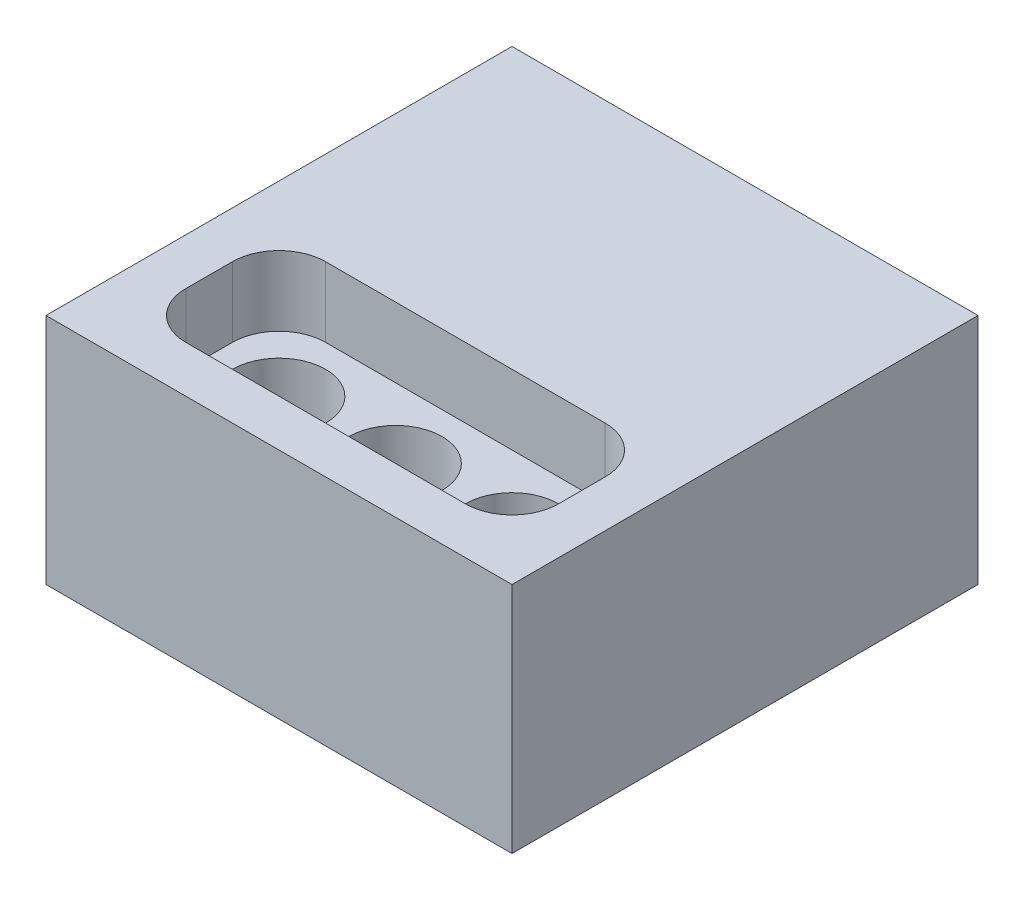
SolidWorks part; units mm, degrees
material "Steel, Hot Worked, AISI 1095"
ref_plane "Front Plane" through (0, 0, 0) normal (0, 0, 1) x (1, 0, 0)
ref_plane "Top Plane" through (0, 0, 0) normal (0, 1, 0) x (1, 0, 0)
ref_plane "Right Plane" through (0, 0, 0) normal (1, 0, 0) x (0, 0, -1)
sketch "Sketch1" plane through (0, 0, 0) normal (0, 1, 0) x (1, 0, 0)
  line L1 (0, 0) -> (100, 0)
  line L2 (0, 0) -> (0, 100)
  line L3 (0, 100) -> (100, 100)
  line L4 (100, 0) -> (100, 100)
  dimension "D1" = 100
  dimension "D2" = 100
extrude "Boss-Extrude1" add sketch "Sketch1" along normal blind 50
sketch "Sketch3" plane through (0, 50, 0) normal (0, 1, 0) x (1, 0, 0)
  line L0 (0, 100) -> (0, 0) construction
  line L1 (10, 10) -> (90, 10)
  line L2 (10, 10) -> (10, 40)
  line L3 (10, 40) -> (90, 40)
  line L4 (90, 10) -> (90, 40)
  line L5 (0, 0) -> (100, 0) construction
  dimension "D1" = 10
  dimension "D2" = 80
  dimension "D3" = 10
  dimension "D4" = 30
extrude "Cut-Extrude2" cut sketch "Sketch3" against normal blind 15
fillet "Fillet1" radius 10 4 edges at (90, 42.5, -10) (90, 42.5, -40) (10, 42.5, -40) (10, 42.5, -10)
sketch "Sketch4" plane through (0, 35, 0) normal (0, 1, 0) x (1, 0, 0)
  line L0 (0, 100) -> (0, 0) construction
  line L1 (0, 0) -> (100, 0) construction
  circle A0 centre (25, 25) radius 10
  circle A2 centre (75, 25) radius 10
  dimension "D1" = 20
  dimension "D2" = 50
  dimension "D4" = 25
  dimension "D5" = 25
extrude "Cut-Extrude3" cut sketch "Sketch4" against normal blind 15
sketch "Sketch5" plane through (0, 35, 0) normal (0, 1, 0) x (1, 0, 0)
  line L0 (0, 0) -> (100, 0) construction
  circle A0 centre (50, 25) radius 10
  circle A2 centre (25, 25) radius 10 construction
  dimension "D1" = 20
  dimension "D2" = 25
  dimension "D3" = 25
extrude "Cut-Extrude4" cut sketch "Sketch5" against normal through all
